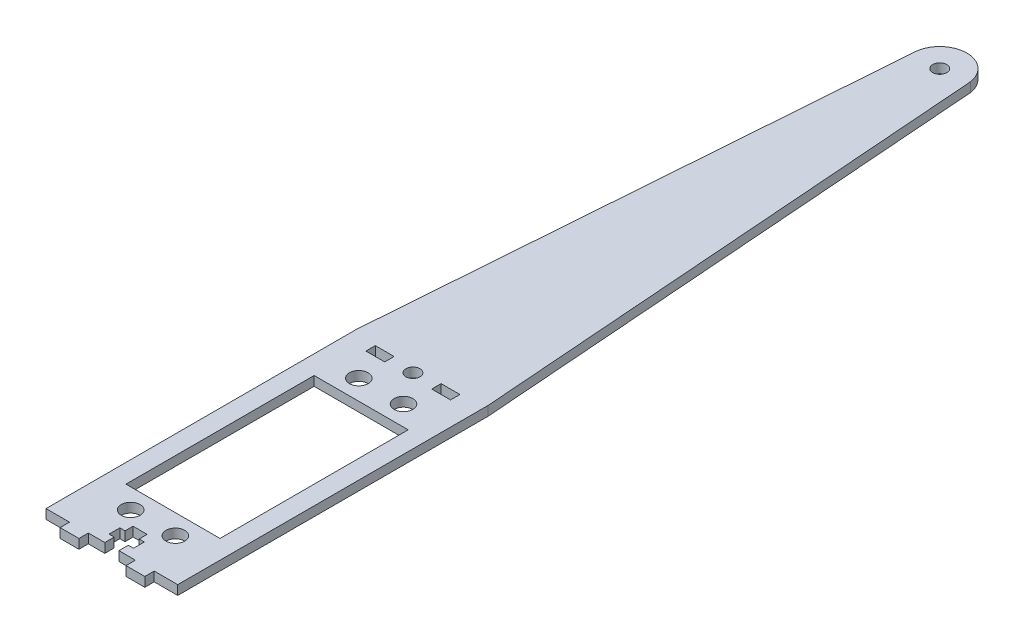
SolidWorks part; units mm, degrees
ref_plane "Front Plane" through (0, 0, 0) normal (0, 0, 1) x (1, 0, 0)
ref_plane "Top Plane" through (0, 0, 0) normal (0, 1, 0) x (1, 0, 0)
ref_plane "Right Plane" through (0, 0, 0) normal (1, 0, 0) x (0, 0, -1)
sketch "Sketch1" plane through (0, 0, 0) normal (0, 1, 0) x (1, 0, 0)
  line L0 (0, 33) -> (28, 33) construction
  line L1 (0, 0) -> (5, 0)
  line L2 (0, 0) -> (0, 66)
  line L3 (0, 66) -> (28, 66)
  line L4 (28, 0) -> (28, 66)
  line L5 (14, 66) -> (14, 0) construction
  line L6 (14, 57.25) -> (18.75, 57.25) construction
  line L7 (4, 13) -> (24, 13)
  line L8 (4, 13) -> (4, 53)
  line L9 (4, 53) -> (24, 53)
  line L10 (24, 13) -> (24, 53)
  line L11 (4, 13) -> (24, 53) construction
  line L12 (4, 53) -> (24, 13) construction
  line L13 (5, 0) -> (5, -2)
  line L19 (12.5, 6) -> (15.5, 6)
  line L20 (12.5, 6) -> (12.5, 4.3)
  line L33 (15.5, 6) -> (15.5, 4.3)
  line L34 (12.5, 6) -> (15.5, 0) construction
  line L35 (12.5, 0) -> (15.5, 6) construction
  line L36 (15.5, 2) -> (16.6, 2)
  line L38 (15.5, 4.3) -> (16.6, 4.3)
  line L39 (16.6, 2) -> (16.6, 4.3)
  line L41 (19, 0) -> (19, -2)
  line L42 (19, -2) -> (23, -2)
  line L43 (23, 0) -> (23, -2)
  line L44 (9, -2) -> (5, -2)
  line L45 (9, 0) -> (9, -2)
  line L46 (12.5, 2) -> (11.4, 2)
  line L47 (11.4, 2) -> (11.4, 4.3)
  line L48 (12.5, 4.3) -> (11.4, 4.3)
  line L49 (9, 0) -> (12.5, 0)
  line L50 (23, 0) -> (28, 0)
  line L51 (12.5, 2) -> (12.5, 0)
  line L52 (15.5, 2) -> (15.5, 0)
  line L53 (15.5, 0) -> (19, 0)
  line L54 (14, 64) -> (21, 64) construction
  line L55 (5, 65) -> (9, 65)
  line L56 (23, 63) -> (19, 63)
  line L57 (23, 63) -> (23, 65)
  line L58 (23, 65) -> (19, 65)
  line L59 (19, 63) -> (19, 65)
  line L60 (23, 63) -> (19, 65) construction
  line L61 (23, 65) -> (19, 63) construction
  line L62 (9, 63) -> (9, 65)
  line L63 (5, 63) -> (9, 63)
  line L64 (5, 63) -> (5, 65)
  circle A0 centre (18.75, 57.25) radius 2
  circle A1 centre (9.25, 57.25) radius 2
  circle A2 centre (18.75, 8.75) radius 2
  circle A3 centre (9.25, 8.75) radius 2
  circle A6 centre (14, 64) radius 1.5
  point P9 (14, 33)
  point P23 (14, 3)
  point P36 (19, -1)
  dimension "D5" = 4
  dimension "D8" = 5
  dimension "D18" = 3
  dimension "D1" = 28
  dimension "D2" = 66
  dimension "D3" = 20
  dimension "D4" = 40
  dimension "D6" = 4.75
  dimension "D7" = 4.25
  dimension "D9" = 4
  dimension "D10" = 2
  dimension "D11" = 3
  dimension "D12" = 6
  dimension "D13" = 1.1
  dimension "D14" = 2.3
  dimension "D15" = 2
  dimension "D16" = 4
  dimension "D17" = 2
  dimension "D19" = 5
  dimension "D20" = 1
extrude "Boss-Extrude1" add sketch "Sketch1" along normal blind 2
sketch "Sketch2" plane through (0, 2, 0) normal (0, 1, 0) x (1, 0, 0)
  line L0 (14, 66) -> (14, 186) construction
  line L1 (28, 66) -> (0, 66) construction
  line L3 (9, 186) -> (0, 66)
  line L4 (0, 66) -> (28, 66)
  line L5 (28, 66) -> (19, 186)
  arc A0 (19, 186) -> (9, 186) centre (14, 186) ccw
  dimension "D1" = 120
  dimension "D2" = 5
extrude "Boss-Extrude2" add sketch "Sketch2" against normal blind 2
sketch "Sketch4" plane through (0, 2, 0) normal (0, 1, 0) x (1, 0, 0)
  line L0 (28, 66) -> (0, 66) construction
  line L1 (14, 66) -> (14, 176) construction
  line L2 (8.25, 176) -> (19.75, 176) construction
  line L3 (9, 186) -> (0, 66) construction
  line L4 (28, 66) -> (19, 186) construction
  line L6 (1.3362, 176) -> (8.25, 176)
  line L7 (1.3362, 176) -> (1.3362, 198.8061)
  line L8 (1.3362, 198.8061) -> (26.6906, 198.8061)
  line L9 (26.6906, 176) -> (26.6906, 198.8061)
  line L10 (19.75, 176) -> (26.6906, 176)
  circle A0 centre (14, 176) radius 1.5
  arc A1 (8.25, 176) -> (19.75, 176) centre (14, 176) cw
  dimension "D1" = 3
  dimension "D2" = 110
extrude "Cut-Extrude1" cut sketch "Sketch4" against normal blind 2
